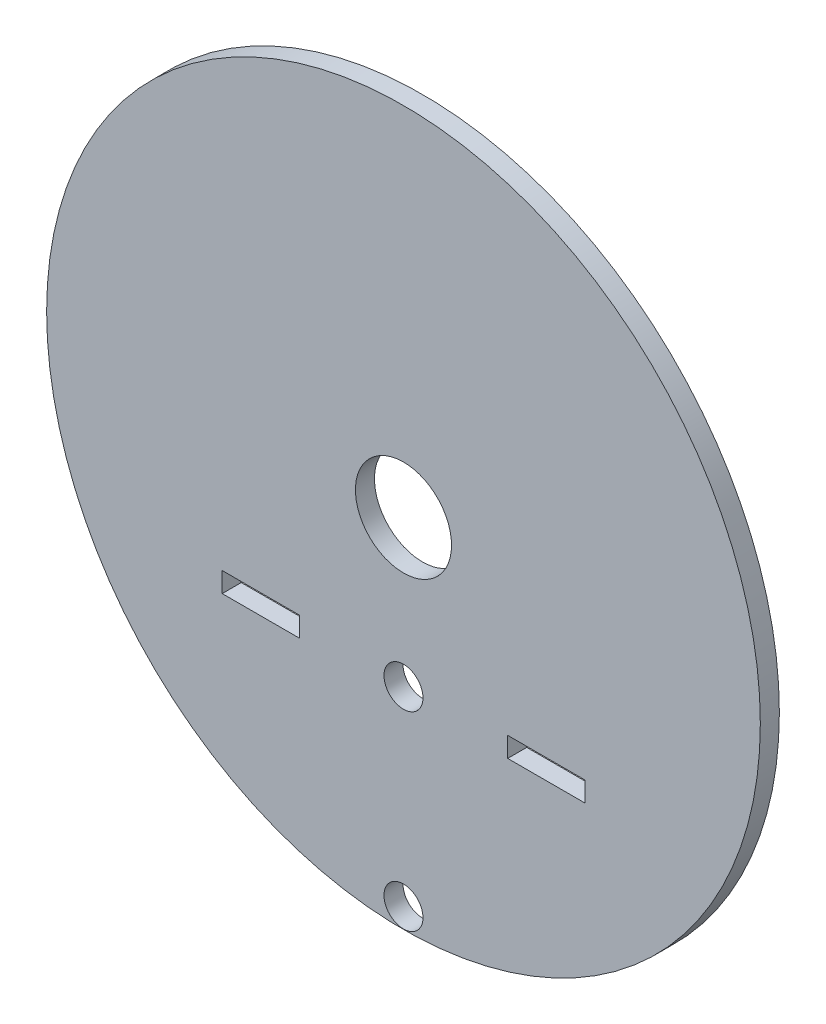
SolidWorks part; units mm, degrees
ref_plane "前视基准面" through (0, 0, 0) normal (0, 0, 1) x (1, 0, 0)
ref_plane "上视基准面" through (0, 0, 0) normal (0, 1, 0) x (1, 0, 0)
ref_plane "右视基准面" through (0, 0, 0) normal (1, 0, 0) x (0, 0, -1)
sketch "草图1" plane through (0, 0, 0) normal (0, 0, 1) x (1, 0, 0)
  line L0 (0, 0) -> (0, 20) construction
  line L1 (0, 20) -> (-15, 20) construction
  line L2 (0, 10) -> (-3.9018, 10) construction
  line L3 (-19.05, 21.05) -> (-10.95, 21.05)
  line L4 (-19.05, 21.05) -> (-19.05, 18.95)
  line L5 (-19.05, 18.95) -> (-10.95, 18.95)
  line L6 (-10.95, 21.05) -> (-10.95, 18.95)
  line L7 (-19.05, 21.05) -> (-10.95, 18.95) construction
  line L8 (-19.05, 18.95) -> (-10.95, 21.05) construction
  line L13 (10.95, 21.05) -> (10.95, 18.95)
  line L14 (19.05, 21.05) -> (10.95, 21.05)
  line L15 (19.05, 21.05) -> (19.05, 18.95)
  line L16 (19.05, 18.95) -> (10.95, 18.95)
  circle A0 centre (0, 0) radius 2.05
  circle A1 centre (0, 20) radius 2.05
  circle A2 centre (0, 35.4) radius 5.05
  circle A4 centre (0, 35.4) radius 12 construction
  circle A6 centre (0, 35.4) radius 39.5 construction
  circle A9 centre (0, 35.4) radius 37.5
  circle A10 centre (0, 20) radius 3.35 construction
  dimension "D1" = 4.1
  dimension "D3" = 4.1
  dimension "D7" = 10.1
  dimension "D9" = 24
  dimension "D10" = 79
  dimension "D11" = 6.7
  dimension "D2" = 20
  dimension "D4" = 15
  dimension "D5" = 8.1
  dimension "D6" = 2.1
  dimension "D8" = 15.4
extrude "凸台-拉伸1" add sketch "草图1" along normal blind 2
